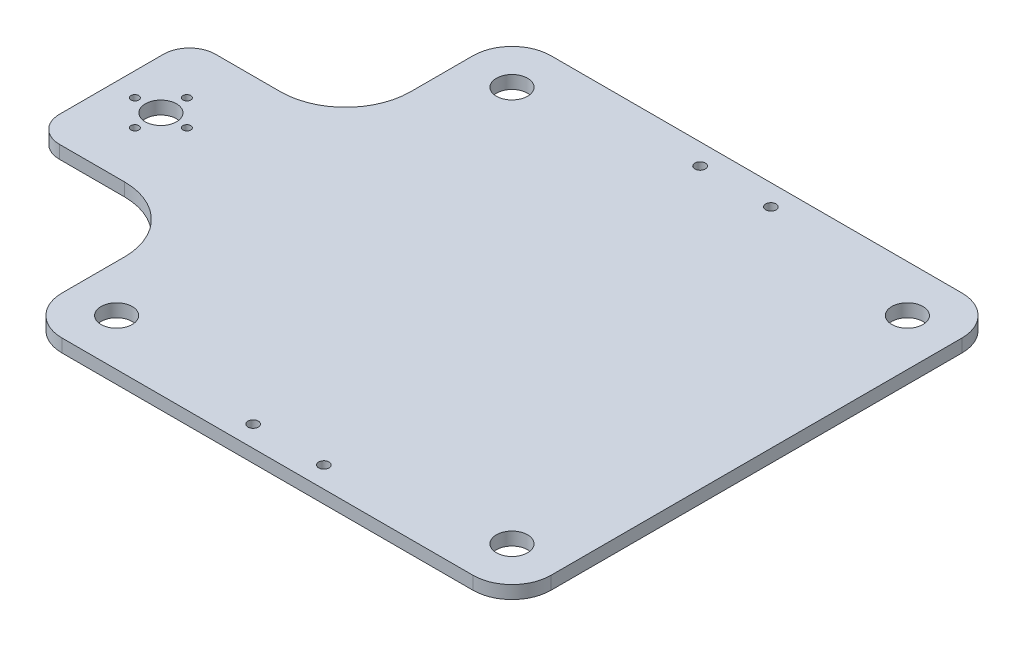
SolidWorks part; units mm, degrees
material "1060 Alloy"
ref_plane "Front Plane" through (0, 0, 0) normal (0, 0, 1) x (1, 0, 0)
ref_plane "Top Plane" through (0, 0, 0) normal (0, 1, 0) x (1, 0, 0)
ref_plane "Right Plane" through (0, 0, 0) normal (1, 0, 0) x (0, 0, -1)
sketch "Sketch1" plane through (0, 0, 0) normal (0, 1, 0) x (1, 0, 0)
  line L2 (13.6098, 85.9289) -> (-13.6098, -85.9289) construction
  line L3 (-79, 94) -> (79, 94)
  line L4 (-94, 79) -> (-94, 30)
  line L11 (-79, -94) -> (79, -94)
  line L12 (94, 79) -> (94, -79)
  line L13 (-94, 94) -> (94, -94) construction
  line L14 (-94, -94) -> (94, 94) construction
  line L15 (13.6098, -85.9289) -> (-13.6098, 85.9289) construction
  line L16 (-94, -30) -> (-154, -30)
  line L17 (-154, -30) -> (-154, 30)
  line L18 (-154, 30) -> (-94, 30)
  line L19 (-94, -30) -> (-94, -79)
  line L20 (13.6098, -85.9289) -> (-13.6098, 85.9289) construction
  line L21 (0, 94) -> (0, -94) construction
  circle A37 centre (0, 0) radius 107.5 construction
  circle A38 centre (-76.014, 76.014) radius 6
  circle A39 centre (76.014, 76.014) radius 6
  circle A40 centre (76.014, -76.014) radius 6
  circle A41 centre (-76.014, -76.014) radius 6
  circle A42 centre (0, 0) radius 94 construction
  circle A43 centre (0, 0) radius 87 construction
  arc A48 (94, 79) -> (79, 94) centre (79, 79) ccw
  arc A49 (94, -79) -> (79, -94) centre (79, -79) cw
  arc A50 (-79, -94) -> (-94, -79) centre (-79, -79) cw
  arc A51 (-94, 79) -> (-79, 94) centre (-79, 79) cw
  circle A52 centre (-135, 0) radius 4 construction
  circle A53 centre (-135, 0) radius 10 construction
  circle A54 centre (-135, -10) radius 1.5
  circle A55 centre (-145, 0) radius 1.5
  circle A56 centre (-135, 10) radius 1.5
  circle A57 centre (-125, 0) radius 1.5
  circle A58 centre (-135, 10) radius 3.5 construction
  circle A59 centre (-135, 0) radius 6
  circle A60 centre (13.6098, 85.9289) radius 2
  circle A61 centre (13.6098, -85.9289) radius 2
  circle A62 centre (-13.6098, 85.9289) radius 2
  circle A63 centre (-13.6098, -85.9289) radius 2
  point P0 (0, 0)
  point P28 (0, 0)
  point P31 (-154, 0)
  point P60 (-135, 0)
  point P61 (0, 0)
  point P63 (0, 0)
  dimension "D1" = 215
  dimension "D2" = 12
  dimension "D4" = 174
  dimension "D5" = 9
  dimension "D6" = 4
  dimension "D8" = 15
  dimension "D9" = 60
  dimension "D11" = 8
  dimension "D12" = 20
  dimension "D13" = 3
  dimension "D14" = 4
  dimension "D10" = 60
  dimension "D15" = 7
  dimension "D7" = 18
  dimension "D3" = 188
  dimension "D16" = 2
  dimension "D17" = 135
  dimension "D18" = 215
  dimension "D19" = 152.028
extrude "Boss-Extrude1" add sketch "Sketch1" along normal mid plane 5
fillet "Fillet1" radius 25 2 edges at (-94, 0, 30) (-94, 0, -30)
fillet "Fillet2" radius 10 2 edges at (-154, 0, 30) (-154, 0, -30)
